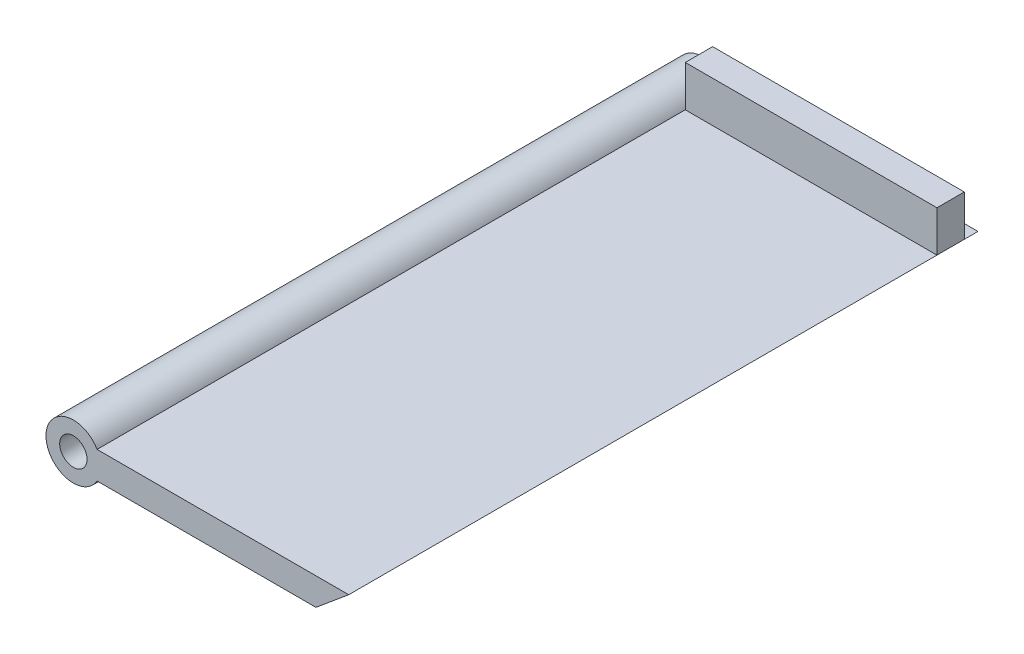
SolidWorks part; units mm, degrees
ref_plane "Front Plane" through (0, 0, 0) normal (0, 0, 1) x (1, 0, 0)
ref_plane "Top Plane" through (0, 0, 0) normal (0, 1, 0) x (1, 0, 0)
ref_plane "Right Plane" through (0, 0, 0) normal (1, 0, 0) x (0, 0, -1)
sketch "Sketch1" plane through (0, 0, 0) normal (0, 0, 1) x (1, 0, 0)
  line L0 (40.4201, 3.0555) -> (32.8001, -3.2945)
  line L1 (-17.9999, 3.0555) -> (40.4201, 3.0555)
  line L3 (-17.9999, -3.2945) -> (32.8001, -3.2945)
  arc A0 (-17.9999, 3.0555) -> (-17.9999, -3.2945) centre (-23.4992, -0.1195) ccw
  circle A1 centre (-23.4992, -0.1195) radius 3.175
  dimension "D1" = 12.7
  dimension "D2" = 6.35
extrude "Boss-Extrude1" add sketch "Sketch1" along normal blind 146.05
ref_plane "Plane1" through (0, 0, 3.175) normal (0, 0, 1) x (1, 0, 0)
sketch "Sketch2" plane through (0, 0, 3.175) normal (0, 0, 1) x (1, 0, 0)
  line L0 (40.4201, 3.0555) -> (-17.9999, 3.0555) construction
  line L2 (-14.8249, 3.0555) -> (-14.8249, 9.4055)
  line L3 (-14.8249, 9.4055) -> (37.2451, 9.4055)
  line L4 (37.2451, 3.0555) -> (37.2451, 9.4055)
  line L6 (-17.9999, 3.0555) -> (40.4201, 3.0555)
  line L7 (-17.9999, 3.0555) -> (-17.9999, 12.5805)
  line L8 (-17.9999, 12.5805) -> (40.4201, 12.5805)
  line L9 (40.4201, 3.0555) -> (40.4201, 12.5805)
  dimension "D1" = 3.175
  dimension "D2" = 3.175
  dimension "D3" = 3.175
extrude "Boss-Extrude2" add sketch "Sketch2" along normal blind 3.175 contours L6 L9 L8 L7 L2 L3 L4
ref_plane "Plane2" through (0, 0, 6.35) normal (0, 0, 1) x (1, 0, 0)
sketch "Sketch3" plane through (0, 0, 6.35) normal (0, 0, 1) x (1, 0, 0)
  line L1 (-17.9999, 12.5805) -> (40.4201, 12.5805)
  line L2 (-17.9999, 12.5805) -> (-17.9999, 3.0555)
  line L3 (-17.9999, 3.0555) -> (40.4201, 3.0555)
  line L4 (40.4201, 12.5805) -> (40.4201, 3.0555)
extrude "Boss-Extrude3" add sketch "Sketch3" along normal blind 3.175
